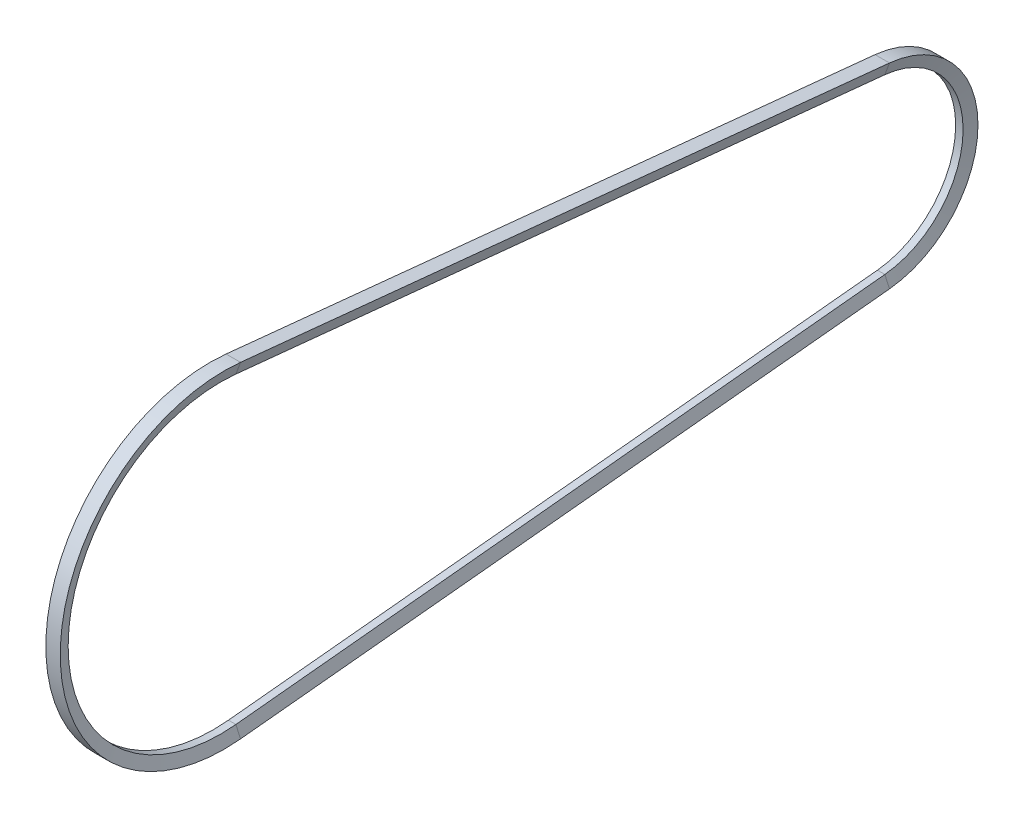
SolidWorks part; units mm, degrees
ref_plane "前视基准面" through (0, 0, 0) normal (0, 0, 1) x (1, 0, 0)
ref_plane "上视基准面" through (0, 0, 0) normal (0, 1, 0) x (1, 0, 0)
ref_plane "右视基准面" through (0, 0, 0) normal (1, 0, 0) x (0, 0, -1)
sketch "草图1" plane through (0, 0, 0) normal (1, 0, 0) x (0, 0, -1)
  line L0 (12.5, 124.3734) -> (507.5, 74.6241)
  line L1 (12.5, -124.3734) -> (507.5, -74.6241)
  line L2 (0, 0) -> (500, 0) construction
  arc A0 (12.5, 124.3734) -> (12.5, -124.3734) centre (0, 0) ccw
  arc A1 (507.5, -74.6241) -> (507.5, 74.6241) centre (500, 0) ccw
  dimension "D1" = 125
  dimension "D2" = 75
  dimension "D3" = 500
sketch "草图2" plane through (0, 0, 0) normal (0, 0, 1) x (1, 0, 0)
  line L0 (-5.5, 125) -> (5.5, 125)
  line L1 (5.5, 125) -> (2.8401, 116.3)
  line L2 (2.8401, 116.3) -> (-2.8401, 116.3)
  line L3 (-2.8401, 116.3) -> (-5.5, 125)
  line L4 (0, 116.3) -> (0, 125) construction
  line L5 (0, -125) -> (0, 125) construction
  dimension "D1" = 11
  dimension "D2" = 8.7
  dimension "D3" = 34
sweep "扫描1" add profiles "草图2" path "草图1"
equation "\"D3@草图1\" = \"D1@距离1@辐板轮_辐板轮.Assembly\""
equation "\"D1@草图2\" = \"bd@草图1@大带轮_辐板轮.Part\" "
equation "\"D2@草图2\" = \"hf@草图1@大带轮_辐板轮.Part\" "
equation "\"D3@草图2\" = \"槽轮角@草图1@大带轮_辐板轮.Part\" "
equation " \"D2@草图1\" = \"dd@草图1@小带轮_辐板轮.Part\"/2"
equation "\"D1@草图1\" = \"dd@草图1@大带轮_辐板轮.Part\" /2"
